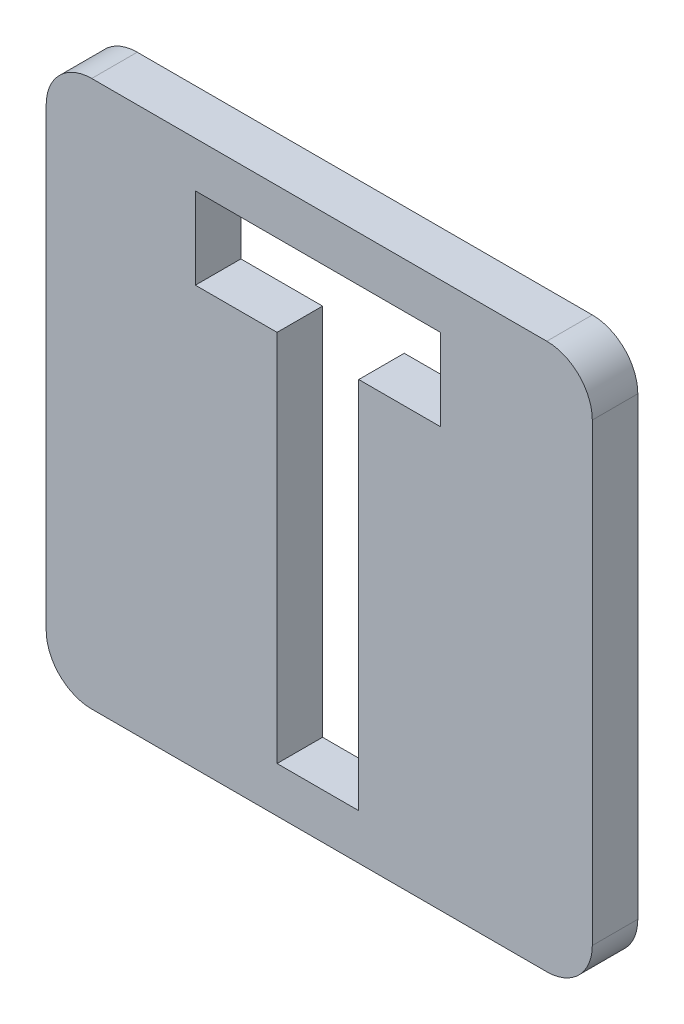
SolidWorks part; units mm, degrees
ref_plane "Front Plane" through (0, 0, 0) normal (0, 0, 1) x (1, 0, 0)
ref_plane "Top Plane" through (0, 0, 0) normal (0, 1, 0) x (1, 0, 0)
ref_plane "Right Plane" through (0, 0, 0) normal (1, 0, 0) x (0, 0, -1)
sketch "Sketch1" plane through (0, 0, 0) normal (0, 0, 1) x (1, 0, 0)
  line L1 (-50, 60) -> (50, 60)
  line L2 (-60, 50) -> (-60, -50)
  line L3 (-50, -60) -> (50, -60)
  line L4 (60, 50) -> (60, -50)
  line L5 (-60, 60) -> (60, -60) construction
  line L6 (-60, -60) -> (60, 60) construction
  arc A0 (-60, -50) -> (-50, -60) centre (-50, -50) ccw
  arc A1 (50, -60) -> (60, -50) centre (50, -50) ccw
  arc A2 (50, 60) -> (60, 50) centre (50, 50) cw
  arc A3 (-50, 60) -> (-60, 50) centre (-50, 50) ccw
  point P0 (0, 0)
  dimension "D3" = 10
  dimension "D1" = 120
  dimension "D2" = 120
extrude "Boss-Extrude1" add sketch "Sketch1" along normal blind 10 contours A3 L2 A0 L3 A1 L4 A2 L1
sketch "Sketch2" plane through (0, 0, 10) normal (0, 0, 1) x (1, 0, 0)
  line L0 (0, 0) -> (0, 40) construction
  line L1 (-50, 50) -> (50, 50) construction
  line L2 (-50, 50) -> (-50, -50) construction
  line L3 (-50, -50) -> (50, -50) construction
  line L4 (50, 50) -> (50, -50) construction
  line L5 (-50, 50) -> (50, -50) construction
  line L6 (-50, -50) -> (50, 50) construction
  line L7 (0, 40) -> (-40, 40) construction
  line L8 (-40, 40) -> (-40, 0) construction
  line L9 (-40, 0) -> (0, 0) construction
  line L11 (0, 20) -> (-20, 20) construction
  line L12 (-20, 40) -> (-20, 20) construction
  circle A0 centre (0, 40) radius 4 construction
  circle A1 centre (0, 20) radius 4 construction
  circle A2 centre (0, 0) radius 4 construction
  circle A3 centre (-20, 20) radius 4 construction
  circle A4 centre (-20, 40) radius 4 construction
  circle A5 centre (-40, 40) radius 4 construction
  circle A6 centre (0, 0) radius 4 construction
  circle A7 centre (20, 0) radius 4 construction
  circle A8 centre (40, 0) radius 4 construction
  circle A9 centre (40, 20) radius 4 construction
  circle A10 centre (40, 40) radius 4 construction
  circle A11 centre (20, 20) radius 4 construction
  circle A12 centre (0, 0) radius 4 construction
  circle A13 centre (0, -20) radius 4 construction
  circle A14 centre (0, -40) radius 4 construction
  circle A15 centre (20, -40) radius 4 construction
  circle A16 centre (40, -40) radius 4 construction
  circle A17 centre (20, -20) radius 4 construction
  circle A18 centre (0, 0) radius 4 construction
  circle A19 centre (-20, 0) radius 4 construction
  circle A20 centre (-40, 0) radius 4 construction
  circle A21 centre (-40, -20) radius 4 construction
  circle A22 centre (-40, -40) radius 4 construction
  circle A23 centre (-20, -20) radius 4 construction
  text T0 "T" font "Century Gothic" height 100
  point P0 (0, 0)
  point P55 (0, 0)
  dimension "D4" = 8
  dimension "D1" = 100
  dimension "D2" = 100
  dimension "D3" = 40
  dimension "D5" = 4
extrude "Cut-Extrude33" cut sketch "Sketch2" against normal blind 10
